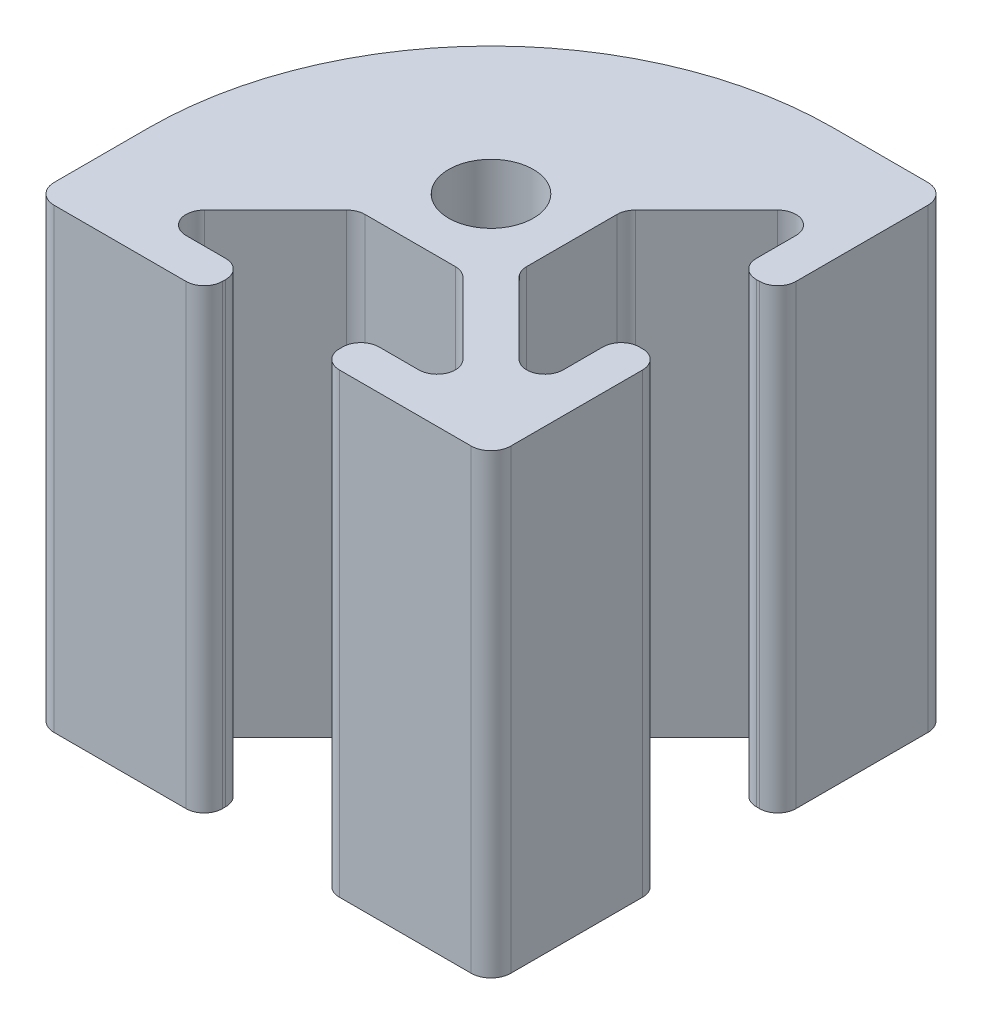
SolidWorks part; units mm, degrees
ref_plane "Front" through (0, 0, 0) normal (0, 0, 1) x (1, 0, 0)
ref_plane "Top" through (0, 0, 0) normal (0, 1, 0) x (1, 0, 0)
ref_plane "Right" through (0, 0, 0) normal (1, 0, 0) x (0, 0, -1)
sketch "Sketch1" plane through (0, 0, 0) normal (0, 0, 1) x (1, 0, 0)
  line L0 (0, 0) -> (0, 25.4)
  dimension "D1" = 25.4
other "10 1012-S(1)"
ref_plane "Plane1" through (0, 0, 0) normal (0, 1, 0) x (-1, 0, 0)
sketch "Sketch11" plane through (0, 0, 0) normal (0, 1, 0) x (-1, 0, 0)
  line L0 (24.2951, 0) -> (16.9672, 0)
  line L1 (0, -1.1049) -> (0, -24.2951) construction
  line L2 (15.9512, -1.016) -> (15.9512, -1.1938)
  line L3 (16.9672, -2.2098) -> (19.1748, -2.2098)
  line L4 (19.8932, -3.9442) -> (15.9308, -7.9066)
  line L5 (15.2124, -8.2042) -> (10.1876, -8.2042)
  line L6 (9.4692, -7.9066) -> (5.5068, -3.9442)
  line L7 (6.2252, -2.2098) -> (8.4328, -2.2098)
  line L8 (9.4488, -1.1938) -> (9.4488, -1.016)
  line L9 (25.4, -6.35) -> (25.4, -1.1049)
  line L10 (6.35, -25.4) -> (1.1049, -25.4)
  line L11 (0, -12.7) -> (12.7, -12.7) construction
  line L12 (12.7, -12.7) -> (12.7, 0) construction
  line L13 (15.9512, -2.2098) -> (12.7, 0) construction
  line L14 (12.7, 0) -> (9.4488, -2.2098) construction
  line L15 (12.7, -12.7) -> (25.4, 0) construction
  line L16 (8.4328, 0) -> (1.1049, 0)
  line L17 (15.9512, 0) -> (12.7, 0) construction
  line L18 (12.7, 0) -> (9.4488, 0) construction
  line L19 (0, -1.1049) -> (0, -8.4328)
  line L20 (1.016, -9.4488) -> (1.1938, -9.4488)
  line L21 (2.2098, -8.4328) -> (2.2098, -6.2252)
  line L22 (3.9442, -5.5068) -> (7.9066, -9.4692)
  line L23 (8.2042, -10.1876) -> (8.2042, -15.2124)
  line L24 (7.9066, -15.9308) -> (3.9442, -19.8932)
  line L25 (2.2098, -19.1748) -> (2.2098, -16.9672)
  line L26 (1.1938, -15.9512) -> (1.016, -15.9512)
  line L27 (0, -16.9672) -> (0, -24.2951) construction
  line L28 (0, -16.9672) -> (0, -24.2951)
  arc A0 (25.4, -6.35) -> (6.35, -25.4) centre (6.35, -6.35) cw
  arc A1 (16.9672, -2.2098) -> (15.9512, -1.1938) centre (16.9672, -1.1938) cw
  arc A2 (16.9672, 0) -> (15.9512, -1.016) centre (16.9672, -1.016) ccw
  arc A3 (8.4328, 0) -> (9.4488, -1.016) centre (8.4328, -1.016) cw
  arc A4 (9.4488, -1.1938) -> (8.4328, -2.2098) centre (8.4328, -1.1938) cw
  arc A5 (5.5068, -3.9442) -> (6.2252, -2.2098) centre (6.2252, -3.2258) cw
  arc A6 (10.1876, -8.2042) -> (9.4692, -7.9066) centre (10.1876, -7.1882) cw
  arc A7 (15.9308, -7.9066) -> (15.2124, -8.2042) centre (15.2124, -7.1882) cw
  arc A8 (19.8932, -3.9442) -> (19.1748, -2.2098) centre (19.1748, -3.2258) ccw
  arc A9 (25.4, -1.1049) -> (24.2951, 0) centre (24.2951, -1.1049) ccw
  arc A10 (1.1049, -25.4) -> (0, -24.2951) centre (1.1049, -24.2951) cw construction
  arc A11 (1.1049, 0) -> (0, -1.1049) centre (1.1049, -1.1049) ccw
  arc A12 (0, -8.4328) -> (1.016, -9.4488) centre (1.016, -8.4328) ccw
  arc A13 (2.2098, -8.4328) -> (1.1938, -9.4488) centre (1.1938, -8.4328) cw
  arc A14 (3.9442, -5.5068) -> (2.2098, -6.2252) centre (3.2258, -6.2252) ccw
  arc A15 (7.9066, -9.4692) -> (8.2042, -10.1876) centre (7.1882, -10.1876) cw
  arc A16 (8.2042, -15.2124) -> (7.9066, -15.9308) centre (7.1882, -15.2124) cw
  arc A17 (3.9442, -19.8932) -> (2.2098, -19.1748) centre (3.2258, -19.1748) cw
  arc A18 (1.1938, -15.9512) -> (2.2098, -16.9672) centre (1.1938, -16.9672) cw
  arc A19 (0, -16.9672) -> (1.016, -15.9512) centre (1.016, -16.9672) cw
  circle A20 centre (12.7, -12.7) radius 2.3546
  arc A21 (1.1049, -25.4) -> (0, -24.2951) centre (1.1049, -24.2951) cw
  point P43 (0, -25.4)
  point P46 (0, 0)
  point P47 (0, 0)
  point P74 (12.7, -12.7)
  dimension "D1" = 25.4
  dimension "D7" = 19.05
  dimension "D10" = 1.016
  dimension "D11" = 1.1049
  dimension "D12" = 1.1049
  dimension "D13" = 1.1049
  dimension "D15" = 4.7091
  dimension "D2" = 6.5024
  dimension "D3" = 8.2042
  dimension "D4" = 2.2098
  dimension "D5" = 45
  dimension "D6" = 2.2098
  dimension "D8" = 12.7
  dimension "D9" = 25.4
  dimension "D14" = 2
